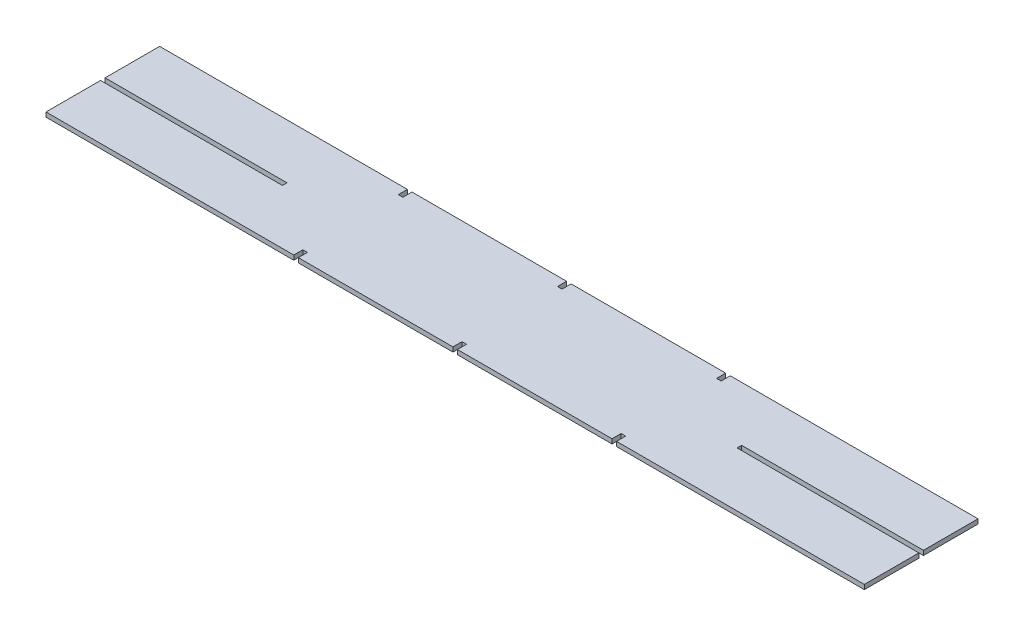
SolidWorks part; units mm, degrees
ref_plane "Front Plane" through (0, 0, 0) normal (0, 0, 1) x (1, 0, 0)
ref_plane "Top Plane" through (0, 0, 0) normal (0, 1, 0) x (1, 0, 0)
ref_plane "Right Plane" through (0, 0, 0) normal (1, 0, 0) x (0, 0, -1)
sketch "Sketch1" plane through (0, 0, 0) normal (0, 1, 0) x (1, 0, 0)
  line L0 (-50, 0) -> (0, 0) construction
  line L1 (-90, 12.5) -> (90, 12.5) construction
  line L2 (-90, 12.5) -> (-90, -12.5) construction
  line L3 (-90, -12.5) -> (90, -12.5) construction
  line L4 (90, 12.5) -> (90, -12.5) construction
  line L5 (-90, 12.5) -> (90, -12.5) construction
  line L6 (-90, -12.5) -> (90, 12.5) construction
  line L7 (-90, 10.5) -> (90, 10.5) construction
  line L9 (-90, -10.5) -> (90, -10.5) construction
  line L11 (-0.5, 12.5) -> (-0.5, 10.5)
  line L12 (-0.5, 10.5) -> (0.5, 10.5)
  line L13 (0.5, 10.5) -> (0.5, 12.5)
  line L14 (0.5, 12.5) -> (34.5, 12.5)
  line L15 (34.5, 12.5) -> (34.5, 10.5)
  line L16 (34.5, 10.5) -> (35.5, 10.5)
  line L17 (35.5, 10.5) -> (35.5, 12.5)
  line L18 (35.5, 12.5) -> (90, 12.5)
  line L19 (90, 12.5) -> (90, 0.5)
  line L20 (90, 0.5) -> (50, 0.5)
  line L21 (50, 0.5) -> (50, -0.5)
  line L22 (50, -0.5) -> (90, -0.5)
  line L23 (90, -0.5) -> (90, -12.5)
  line L24 (90, -12.5) -> (35.5, -12.5)
  line L25 (35.5, -12.5) -> (35.5, -10.5)
  line L26 (35.5, -10.5) -> (34.5, -10.5)
  line L27 (34.5, -10.5) -> (34.5, -12.5)
  line L28 (34.5, -12.5) -> (0.5, -12.5)
  line L29 (0.5, -12.5) -> (0.5, -10.5)
  line L30 (0.5, -10.5) -> (-0.5, -10.5)
  line L31 (-0.5, -10.5) -> (-0.5, -12.5)
  line L32 (-0.5, -12.5) -> (-34.5, -12.5)
  line L33 (-34.5, -12.5) -> (-34.5, -10.5)
  line L34 (-34.5, -10.5) -> (-35.5, -10.5)
  line L35 (-35.5, -10.5) -> (-35.5, -12.5)
  line L36 (-35.5, -12.5) -> (-90, -12.5)
  line L37 (-90, -12.5) -> (-90, -0.5)
  line L38 (-90, -0.5) -> (-50, -0.5)
  line L39 (-50, -0.5) -> (-50, 0.5)
  line L40 (-50, 0.5) -> (-90, 0.5)
  line L41 (-90, 0.5) -> (-90, 12.5)
  line L42 (-90, 12.5) -> (-35.5, 12.5)
  line L43 (-35.5, 12.5) -> (-35.5, 10.5)
  line L44 (-35.5, 10.5) -> (-34.5, 10.5)
  line L45 (-34.5, 10.5) -> (-34.5, 12.5)
  line L46 (-34.5, 12.5) -> (-0.5, 12.5)
  line L47 (0, 0) -> (0, 10.5) construction
  line L48 (0, -10.5) -> (0, 0) construction
  line L50 (-35, 10.5) -> (-35, -10.5) construction
  line L52 (-50, 0) -> (-90, 0) construction
  line L53 (0, 0) -> (50, 0) construction
  line L54 (50, 0) -> (90, 0) construction
  line L56 (35, 10.5) -> (35, -10.5) construction
  line L57 (35, -10.5) -> (35, -12.5) construction
  point P0 (0, 0)
  point P18 (0, 0)
  point P55 (44.4604, -10.5)
  dimension "D1" = 25
  dimension "D2" = 180
  dimension "D3" = 40
  dimension "D4" = 1
  dimension "D5" = 40
  dimension "D6" = 1
  dimension "D7" = 1
  dimension "D8" = 15
  dimension "D9" = 1
  dimension "D10" = 40
  dimension "D11" = 2
  dimension "D12" = 2
  dimension "D13" = 1
  dimension "D14" = 15
extrude "Boss-Extrude1" add sketch "Sketch1" along normal blind 1
